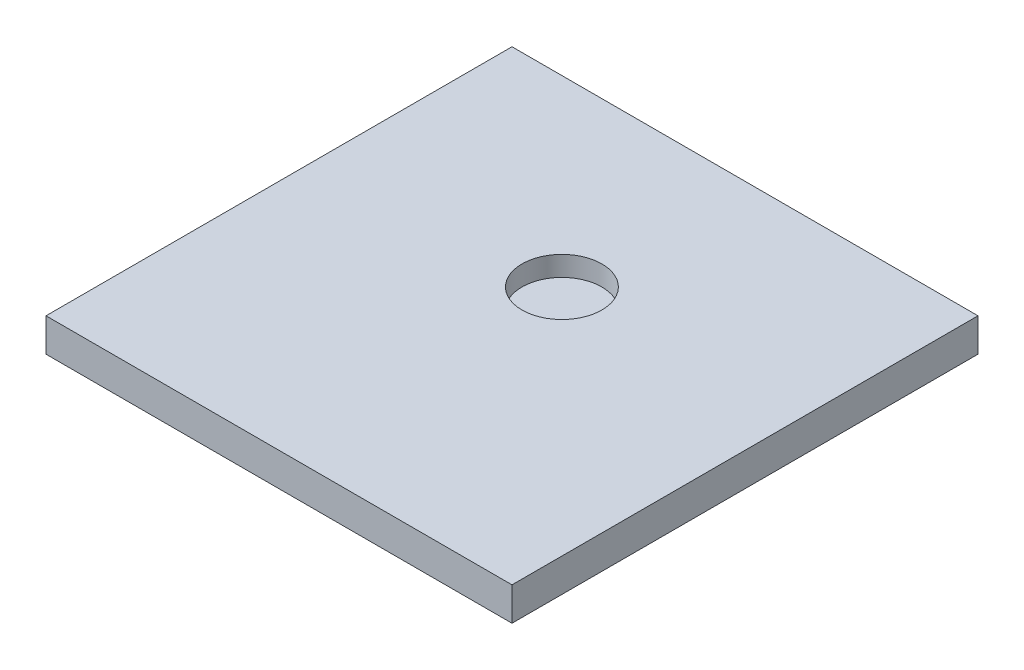
SolidWorks part; units mm, degrees
ref_plane "Front Plane" through (0, 0, 0) normal (0, 0, 1) x (1, 0, 0)
ref_plane "Top Plane" through (0, 0, 0) normal (0, 1, 0) x (1, 0, 0)
ref_plane "Right Plane" through (0, 0, 0) normal (1, 0, 0) x (0, 0, -1)
sketch "Sketch1" plane through (0, 0, 0) normal (0, 1, 0) x (1, 0, 0)
  line L1 (-89.0864, 133.1131) -> (88.7136, 133.1131)
  line L2 (-89.0864, 133.1131) -> (-89.0864, -44.6869)
  line L3 (-89.0864, -44.6869) -> (88.7136, -44.6869)
  line L4 (88.7136, 133.1131) -> (88.7136, -44.6869)
extrude "Boss-Extrude1" add sketch "Sketch1" against normal blind 12.7
sketch "Sketch2" plane through (0, 0, 0) normal (0, 1, 0) x (1, 0, 0)
  circle A0 centre (-0.1864, 63.2631) radius 15.24
extrude "Cut-Extrude1" cut sketch "Sketch2" against normal blind 7.62 contours A0
